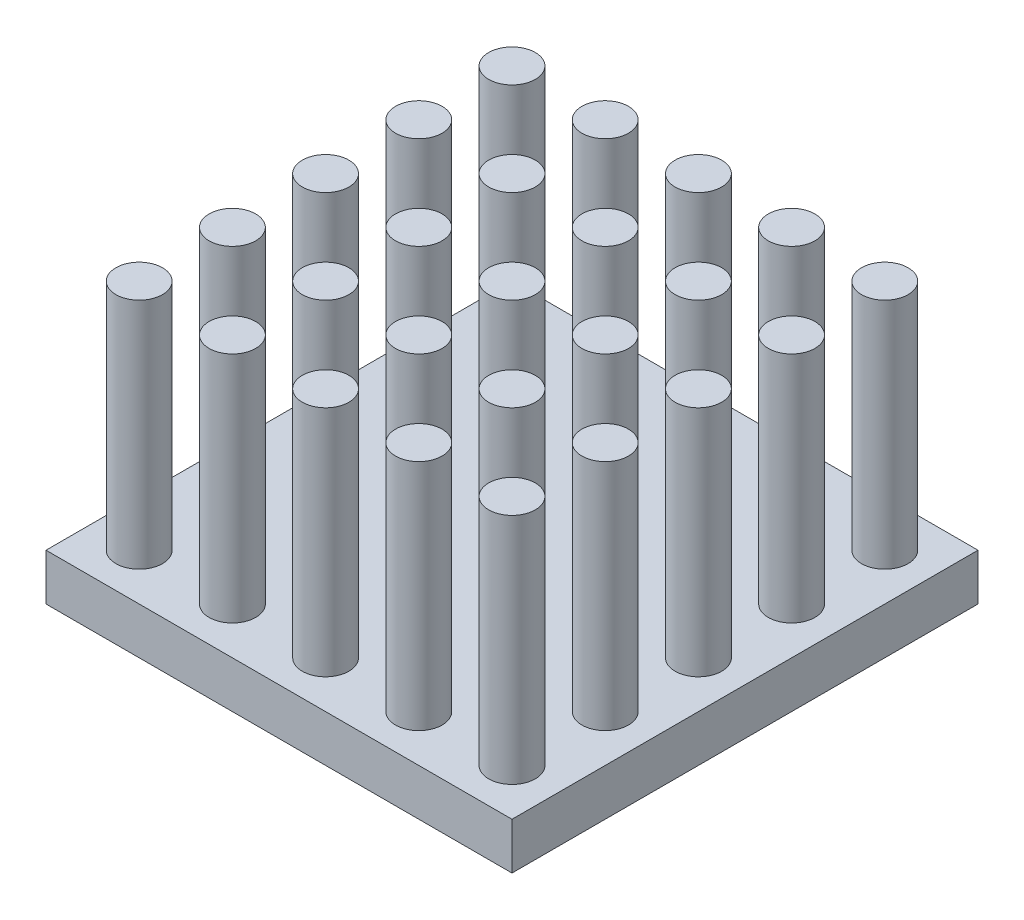
SolidWorks part; units mm, degrees
ref_plane "前基準面" through (0, 0, 0) normal (0, 0, 1) x (1, 0, 0)
ref_plane "上基準面" through (0, 0, 0) normal (0, 1, 0) x (1, 0, 0)
ref_plane "右基準面" through (0, 0, 0) normal (1, 0, 0) x (0, 0, -1)
sketch "草圖1" plane through (0, 0, 0) normal (0, 1, 0) x (1, 0, 0)
  line L1 (-5, 5) -> (5, 5)
  line L2 (-5, 5) -> (-5, -5)
  line L3 (-5, -5) -> (5, -5)
  line L4 (5, 5) -> (5, -5)
  line L5 (-5, 5) -> (5, -5) construction
  line L6 (-5, -5) -> (5, 5) construction
  point P0 (0, 0)
  dimension "D1" = 10
  dimension "D2" = 10
extrude "填料-伸長1" add sketch "草圖1" along normal blind 1 contours L2 L3 L4 L1
sketch "草圖2" plane through (0, 1, 0) normal (0, 1, 0) x (1, 0, 0)
  line L0 (-5, 5) -> (5, 5) construction
  line L2 (-5, 5) -> (-5, -5) construction
  circle A0 centre (-4, 4) radius 0.5
  dimension "D1" = 1
  dimension "D2" = 1
  dimension "D3" = 1
extrude "填料-伸長2" add sketch "草圖2" along normal blind 5
pattern_linear "直線複製排列1" count 5 spacing 2 along (1, 0, 0) of "填料-伸長2"
pattern_linear "直線複製排列2" count 5 spacing 2 along (0, 0, 1) of "填料-伸長2", "直線複製排列1"
